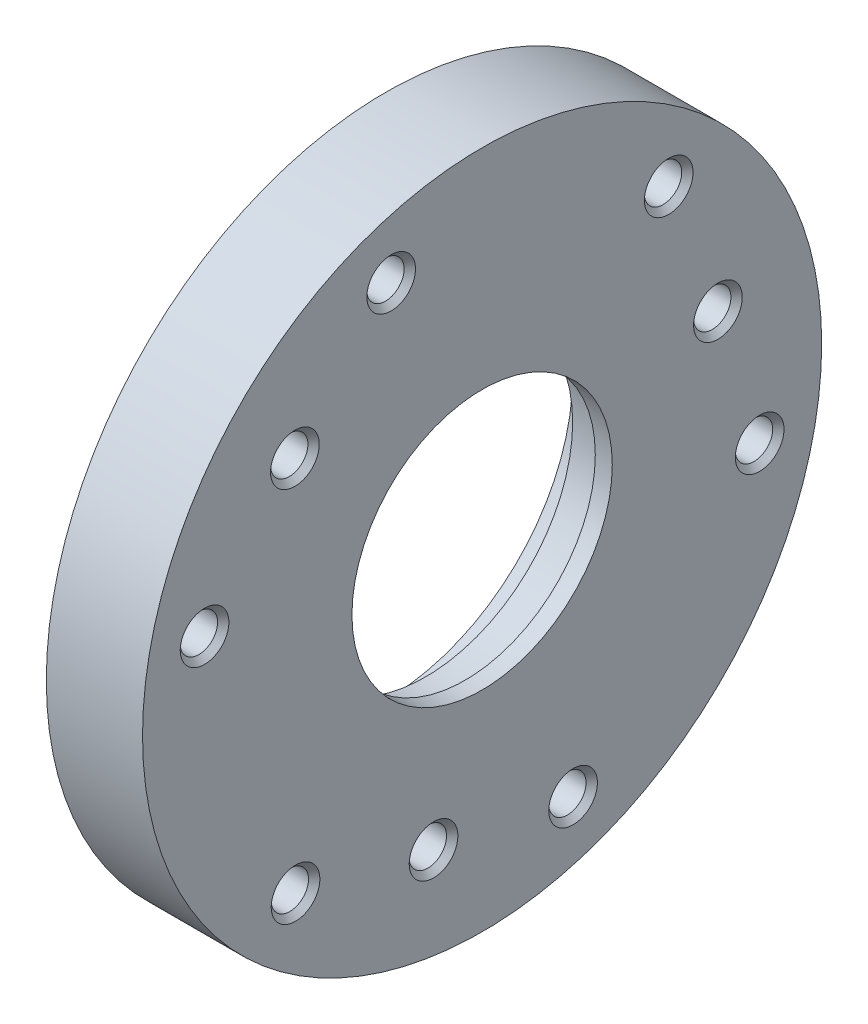
SolidWorks part; units mm, degrees
ref_plane "Front Plane" through (0, 0, 0) normal (0, 0, 1) x (1, 0, 0)
ref_plane "Top Plane" through (0, 0, 0) normal (0, 1, 0) x (1, 0, 0)
ref_plane "Right Plane" through (0, 0, 0) normal (1, 0, 0) x (0, 0, -1)
sketch "Sketch1" plane through (0, 0, 0) normal (0, 0, 1) x (1, 0, 0)
  line L0 (0, 0) -> (14, 0) construction
  line L1 (0, 60) -> (0, 33)
  line L2 (0, 33) -> (7, 33)
  line L3 (7, 33) -> (7, 26)
  line L4 (7, 26) -> (14, 26)
  line L5 (14, 26) -> (14, 23)
  line L6 (14, 23) -> (17, 23)
  line L7 (17, 23) -> (17, 60)
  line L8 (17, 60) -> (0, 60)
  dimension "D1" = 17
  dimension "D2" = 26
  dimension "D3" = 7
  dimension "D4" = 3
  dimension "D5" = 60
  dimension "D6" = 33
  dimension "D7" = 3
revolve "Revolve1" add sketch "Sketch1" angle 360 about L0
sketch "Sketch2" plane through (0, 0, 0) normal (-1, 0, 0) x (0, 0, 1)
  circle A0 centre (0, 0) radius 40 construction
  circle A1 centre (0, 40) radius 2.5
  circle A2 centre (15.3073, 36.9552) radius 2.5
  circle A3 centre (28.2843, 28.2843) radius 2.5
  circle A4 centre (36.9552, 15.3073) radius 2.5
  circle A5 centre (40, 0) radius 2.5
  circle A6 centre (36.9552, -15.3073) radius 2.5
  circle A7 centre (28.2843, -28.2843) radius 2.5
  circle A8 centre (15.3073, -36.9552) radius 2.5
  circle A9 centre (0, -40) radius 2.5
  circle A10 centre (-15.3073, -36.9552) radius 2.5
  circle A11 centre (-28.2843, -28.2843) radius 2.5
  circle A12 centre (-36.9552, -15.3073) radius 2.5
  circle A13 centre (-40, 0) radius 2.5
  circle A14 centre (-36.9552, 15.3073) radius 2.5
  circle A15 centre (-28.2843, 28.2843) radius 2.5
  circle A16 centre (-15.3073, 36.9552) radius 2.5
  point P37 (0, 0)
  dimension "D1" = 80
  dimension "D2" = 5
  dimension "D3" = 16
extrude "Cut-Extrude1" cut sketch "Sketch2" against normal blind 4
sketch "Sketch3" plane through (17, 0, 0) normal (1, 0, 0) x (0, 0, -1)
  circle A0 centre (49.0393, -9.7545) radius 3.075
  circle A1 centre (16.072, -47.3465) radius 3.075
  circle A2 centre (-32.9673, -37.592) radius 3.075
  circle A3 centre (-49.0393, 9.7545) radius 3.075
  circle A4 centre (-16.072, 47.3465) radius 3.075
  circle A5 centre (32.9673, 37.592) radius 3.075
  point P20 (0, 0)
  dimension "D2" = 6.15
  dimension "D1" = 6
extrude "Cut-Extrude4" cut sketch "Sketch3" against normal through all
sketch "Sketch4" [suppressed] plane through (17, 0, 0) normal (1, 0, 0) x (0, 0, -1)
  circle A0 centre (32.9673, 37.592) radius 5.25
  circle A1 centre (49.0393, -9.7545) radius 5.25
  circle A2 centre (16.072, -47.3465) radius 5.25
  circle A3 centre (-32.9673, -37.592) radius 5.25
  circle A4 centre (-49.0393, 9.7545) radius 5.25
  circle A5 centre (-16.072, 47.3465) radius 5.25
  point P20 (0, 0)
  dimension "D1" = 10.5
  dimension "D2" = 6
extrude "Cut-Extrude5" [suppressed] cut sketch "Sketch4" against normal blind 4.5
sketch "Sketch5" plane through (17, 0, 0) normal (1, 0, 0) x (0, 0, -1)
  line L0 (32.9673, 37.592) -> (0, 0) construction
  line L1 (0, 0) -> (41.6649, 14.1433) construction
  circle A0 centre (32.9673, 37.592) radius 3.3
  circle A1 centre (49.0393, -9.7545) radius 3.3
  circle A2 centre (16.072, -47.3465) radius 3.3
  circle A3 centre (-32.9673, -37.592) radius 3.3
  circle A4 centre (-49.0393, 9.7545) radius 3.3
  circle A5 centre (-16.072, 47.3465) radius 3.3
  circle A8 centre (0, 0) radius 44 construction
  circle A9 centre (41.6649, 14.1433) radius 3.3
  circle A10 centre (-8.584, -43.1546) radius 3.3
  circle A11 centre (-33.081, 29.0112) radius 3.3
  point P19 (0, 0)
  point P33 (0, 0)
  dimension "D1" = 6.6
  dimension "D4" = 88
  dimension "D5" = 30
  dimension "D2" = 6
  dimension "D3" = 3
extrude "Cut-Extrude6" cut sketch "Sketch5" against normal blind 10
chamfer "Chamfer1" distance 1 angle 45 9 edges at (17, 47.3465, 12.772) (17, 29.0112, 29.781) (17, 9.7545, 45.7393) (17, -37.592, 29.6673) (17, -43.1546, 5.284) (17, -47.3465, -19.372) (17, -9.7545, -52.3393) (17, 14.1433, -44.9649) (17, 37.592, -36.2673)
sketch "Sketch6" [suppressed] plane through (17, 0, 0) normal (1, 0, 0) x (0, 0, -1)
  circle A0 centre (23.9053, -44.4252) radius 1
  dimension "D1" = 2
extrude "Cut-Extrude7" [suppressed] cut sketch "Sketch6" against normal blind 1
sketch "Sketch7" plane through (0, 0, 0) normal (-1, 0, 0) x (0, 0, 1)
  circle A0 centre (39.0864, -31.8954) radius 1
  dimension "D1" = 2
extrude "Cut-Extrude8" cut sketch "Sketch7" against normal blind 1
equation "\"R_ROLL\"= 5mm"
equation "\"D_SUN\"= 80mm"
equation "\"NUM_ROLL\"= 16"
equation "\"RHO\"= 1mm"
equation "\"D_SHAFT\"= 15mm"
equation "\"D_OUTPUT\"= 40mm"
equation "\"NUM_OUT\"= 6"
equation "\"R_OUT_ROLL\"= 5mm"
equation "\"D1@Sketch2\"=\"D_SUN\""
equation "\"D3@Sketch2\"=\"NUM_ROLL\""
